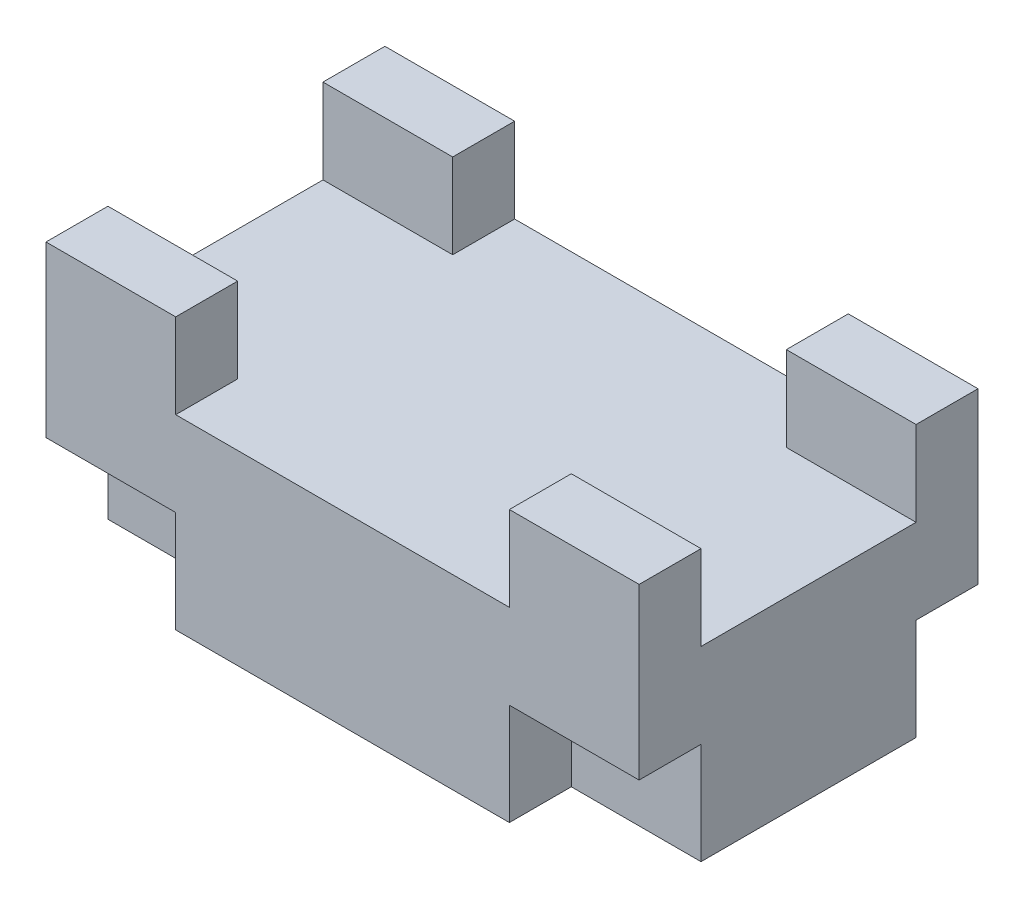
SolidWorks part; units mm, degrees
ref_plane "Front Plane" through (0, 0, 0) normal (0, 0, 1) x (1, 0, 0)
ref_plane "Top Plane" through (0, 0, 0) normal (0, 1, 0) x (1, 0, 0)
ref_plane "Right Plane" through (0, 0, 0) normal (1, 0, 0) x (0, 0, -1)
sketch "Sketch1" plane through (0, 0, 0) normal (0, 1, 0) x (1, 0, 0)
  line L0 (87.5, 31.7241) -> (49.2266, 31.7241)
  line L1 (-87.5, -50) -> (87.5, -50)
  line L2 (-87.5, -50) -> (-87.5, 50)
  line L3 (-87.5, 50) -> (87.5, 50)
  line L4 (87.5, -50) -> (87.5, 50)
  line L5 (-87.5, -50) -> (87.5, 50) construction
  line L6 (-87.5, 50) -> (87.5, -50) construction
  line L7 (49.2266, 31.7241) -> (49.2266, 50)
  line L8 (87.5, 0) -> (-87.5, 0) construction
  line L9 (0, 50) -> (0, -50) construction
  line L10 (49.2266, -31.7241) -> (49.2266, -50)
  line L11 (87.5, -31.7241) -> (49.2266, -31.7241)
  line L12 (-49.2266, -31.7241) -> (-49.2266, -50)
  line L13 (-87.5, -31.7241) -> (-49.2266, -31.7241)
  line L14 (-49.2266, 31.7241) -> (-49.2266, 50)
  line L15 (-87.5, 31.7241) -> (-49.2266, 31.7241)
  point P0 (0, 0)
  dimension "D1" = 175
  dimension "D2" = 100
extrude "Boss-Extrude1" add sketch "Sketch1" along normal blind 55 contours L15 L2 L13 L12 L1 L10 L11 L4 L0 L7 L3 L14
sketch "Sketch3" plane through (0, 55, 0) normal (0, 1, 0) x (1, 0, 0)
  line L0 (-49.2266, 50) -> (-49.2266, 31.7241)
  line L5 (-87.5, -50) -> (87.5, 50) construction
  line L6 (-87.5, 50) -> (87.5, -50) construction
  line L7 (-49.2266, 31.7241) -> (-87.5, 31.7241)
  line L8 (-49.2266, 50) -> (-87.5, 50)
  line L9 (-87.5, 50) -> (-87.5, 31.7241)
  line L10 (-87.5, -31.7241) -> (-87.5, -50)
  line L11 (-87.5, -50) -> (-49.2266, -50)
  line L12 (-49.2266, -31.7241) -> (-49.2266, -50) construction
  line L13 (-49.2266, -50) -> (49.2266, -50) construction
  line L14 (-49.2266, -50) -> (-49.2266, -31.7241)
  line L15 (-87.5, -31.7241) -> (-49.2266, -31.7241) construction
  line L16 (-49.2266, -31.7241) -> (-87.5, -31.7241)
  line L17 (49.2266, -50) -> (49.2266, -31.7241)
  line L18 (49.2266, -31.7241) -> (87.5, -31.7241)
  line L23 (87.5, 31.7241) -> (49.2266, 31.7241)
  line L24 (49.2266, 31.7241) -> (49.2266, 50)
  line L25 (49.2266, 50) -> (87.5, 50)
  line L26 (87.5, 50) -> (87.5, 31.7241)
  line L27 (87.5, -31.7241) -> (87.5, -50)
  line L28 (87.5, -50) -> (49.2266, -50)
  point P0 (0, 0)
extrude "Boss-Extrude2" add sketch "Sketch3" along normal blind 25 and the other way blind 25
